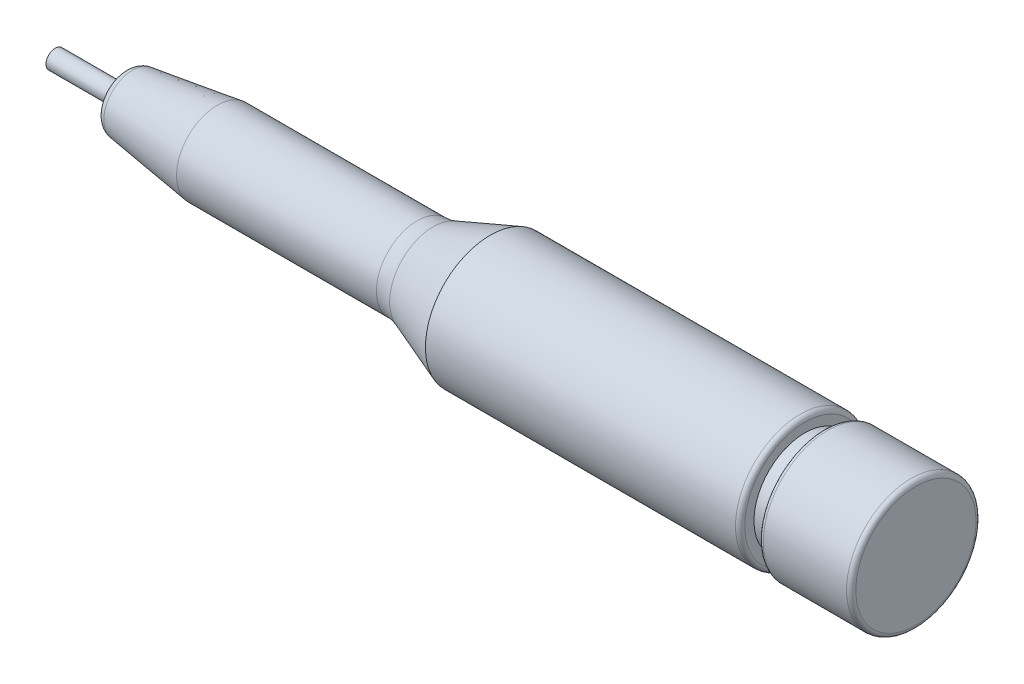
SolidWorks part; units mm, degrees
ref_plane "Plano frontal" through (0, 0, 0) normal (0, 0, 1) x (1, 0, 0)
ref_plane "Plano superior" through (0, 0, 0) normal (0, 1, 0) x (1, 0, 0)
ref_plane "Plano direito" through (0, 0, 0) normal (1, 0, 0) x (0, 0, -1)
sketch "Esboço1" plane through (0, 0, 0) normal (0, 0, 1) x (1, 0, 0)
  line L0 (0, 0) -> (0, 1)
  line L1 (0, 1) -> (7.5, 1)
  line L2 (7.5, 1) -> (7.5, 3)
  line L3 (7.5, 3) -> (17.5, 4.4)
  line L4 (17.5, 4.4) -> (40, 4.4)
  line L6 (47, 7) -> (81, 7)
  line L7 (81, 7) -> (81, 5.5)
  line L8 (81, 5.5) -> (83, 5.5)
  line L13 (40, 4.4) -> (47, 7)
  line L14 (83, 5.5) -> (83, 7)
  line L15 (83, 7) -> (93, 7)
  line L16 (93, 7) -> (93, 0)
  line L17 (93, 0) -> (0, 0)
  dimension "D1" = 1
  dimension "D2" = 7.5
  dimension "D3" = 2
  dimension "D4" = 7
  dimension "D5" = 10
  dimension "D6" = 10
  dimension "D7" = 22.5
  dimension "D8" = 7
  dimension "D9" = 34
  dimension "D10" = 1.5
  dimension "D11" = 2
  dimension "D12" = 4.4
  dimension "D13" = 93
  dimension "D14" = 7
revolve "Revolução1" add sketch "Esboço1" angle 360 about L17
cosmetic thread "Representação de rosca1" parameters "D1"=39.8, "D2"=11.797
fillet "Filete1" radius 5 1 edges at (40, 0, -4.4)
fillet "Filete3" radius 1 1 edges at (7.5, 0, -3)
fillet "Filete4" radius 0.5 3 edges at (81, 0, -7) (93, 0, -7) (83, 0, -7)
